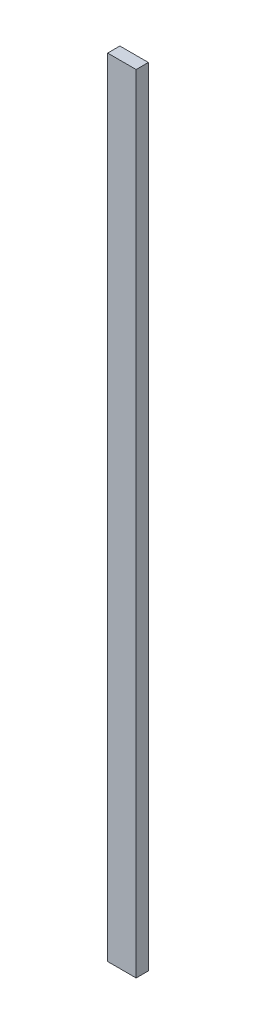
SolidWorks part; units mm, degrees
material "Pine"
ref_plane "Front Plane" through (0, 0, 0) normal (0, 0, 1) x (1, 0, 0)
ref_plane "Top Plane" through (0, 0, 0) normal (0, 1, 0) x (1, 0, 0)
ref_plane "Right Plane" through (0, 0, 0) normal (1, 0, 0) x (0, 0, -1)
sketch "Sketch1" plane through (0, 0, 0) normal (0, 1, 0) x (1, 0, 0)
  line L1 (44.45, -19.05) -> (-44.45, -19.05)
  line L2 (44.45, -19.05) -> (44.45, 19.05)
  line L3 (44.45, 19.05) -> (-44.45, 19.05)
  line L4 (-44.45, -19.05) -> (-44.45, 19.05)
  line L5 (44.45, -19.05) -> (-44.45, 19.05) construction
  line L6 (44.45, 19.05) -> (-44.45, -19.05) construction
  point P0 (0, 0)
  dimension "D1" = 38.1
  dimension "D2" = 88.9
extrude "Boss-Extrude1" add sketch "Sketch1" along normal blind 2454.148
